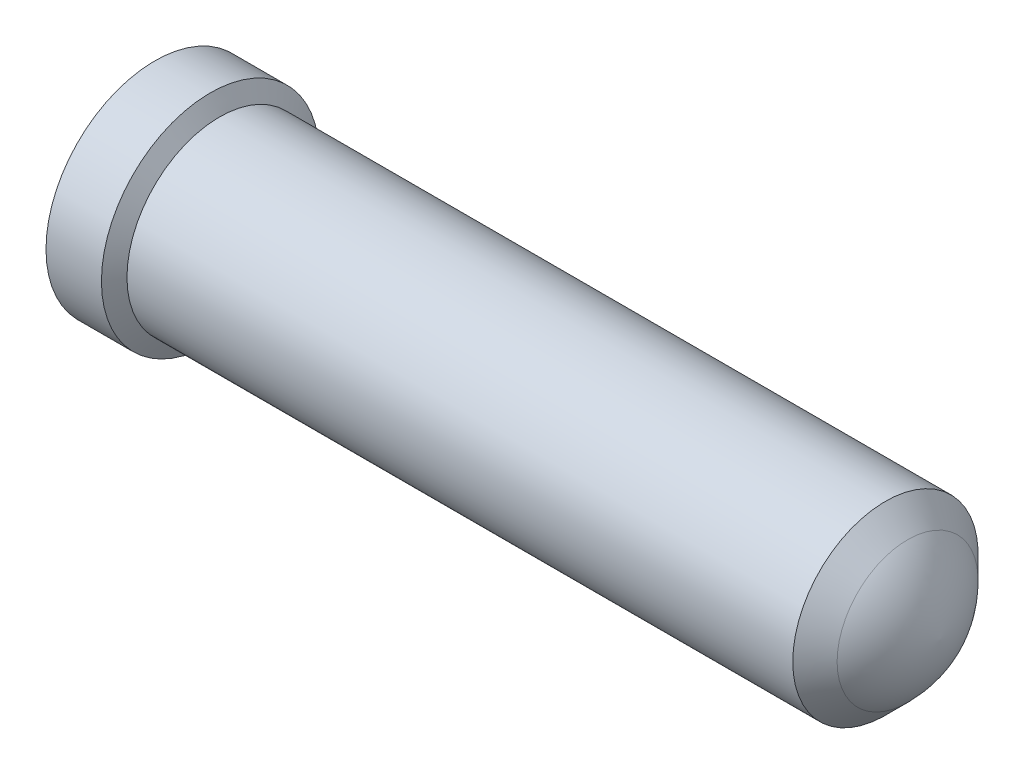
SolidWorks part; units mm, degrees
material "Brass Alloy 385"
ref_plane "Front Plane" through (0, 0, 0) normal (0, 0, 1) x (1, 0, 0)
ref_plane "Top Plane" through (0, 0, 0) normal (0, 1, 0) x (1, 0, 0)
ref_plane "Right Plane" through (0, 0, 0) normal (1, 0, 0) x (0, 0, -1)
sketch "Sketch1" plane through (0, 0, 0) normal (0, 0, 1) x (1, 0, 0)
  line L0 (0, 0) -> (0, 0.6236)
  line L1 (0, 0.6236) -> (0.3175, 0.6236)
  line L2 (0.3175, 0.6236) -> (0.371, 0.5309)
  line L3 (4.1844, 0.5309) -> (0.371, 0.5309)
  line L4 (4.1844, 0.5309) -> (4.3114, 0.4039)
  line L5 (0, 0) -> (4.4958, 0)
  line L6 (0, 0) -> (4.4958, 0) construction
  arc A0 (4.4958, 0) -> (4.3114, 0.4039) centre (3.8624, -0.0452) ccw
revolve "RevolutionAngle1" add sketch "Sketch1" angle 360 about L6
hole_wizard "Hole1" positions "Sketch3" profile "Sketch2" legacy
sketch "Sketch3" plane through (0, 0, 0) normal (-1, 0, 0) x (0, 0, 1)
  point P0 (0, 0)
sketch "Sketch2" plane through (0, 0, 0) normal (0, 1, 0) x (0, 0, 1)
  line L0 (0, 0) -> (0, 1.7987)
  line L1 (0, 1.7987) -> (0.4572, 1.524)
  line L2 (0.4572, 1.524) -> (0.4572, 0.0889)
  line L3 (0.4572, 0.0889) -> (0.5461, 0)
  line L4 (0.5461, 0) -> (0, 0)
  line L5 (0, -14.3089) -> (0, 102.4216) construction
  line L6 (0, 1.7987) -> (-0.4572, 1.524) construction
  line L7 (-0.4572, 0.0889) -> (-0.5461, 0) construction
  dimension "Diameter" = 0.9144
  dimension "Depth" = 1.524
  dimension "C-Sink Diameter" = 1.0922
  dimension "C-Sink Angle" = 90
  dimension "Drill Angle" = 118
hole_wizard "Hole2" positions "3DSketch1" profile "Sketch4" legacy
sketch3d "3DSketch1"
  line L0 (0.3175, 0, 0) -> (0, 0, 0) construction
  point P0 (0, 0, 0)
sketch "Sketch4" plane through (0, 0, 0) normal (0, 1, 0) x (0, 0, 1)
  line L0 (0, 0) -> (0, 2.2051)
  line L1 (0, 2.2051) -> (0.4572, 1.9304)
  line L2 (0.4572, 1.9304) -> (0.4572, 0.0889)
  line L3 (0.4572, 0.0889) -> (0.5461, 0)
  line L4 (0.5461, 0) -> (0, 0)
  line L5 (0, -14.3089) -> (0, 102.4216) construction
  line L6 (0, 2.2051) -> (-0.4572, 1.9304) construction
  line L7 (-0.4572, 0.0889) -> (-0.5461, 0) construction
  dimension "Diameter" = 0.9144
  dimension "Depth" = 1.9304
  dimension "C-Sink Diameter" = 1.0922
  dimension "C-Sink Angle" = 90
  dimension "Drill Angle" = 118
